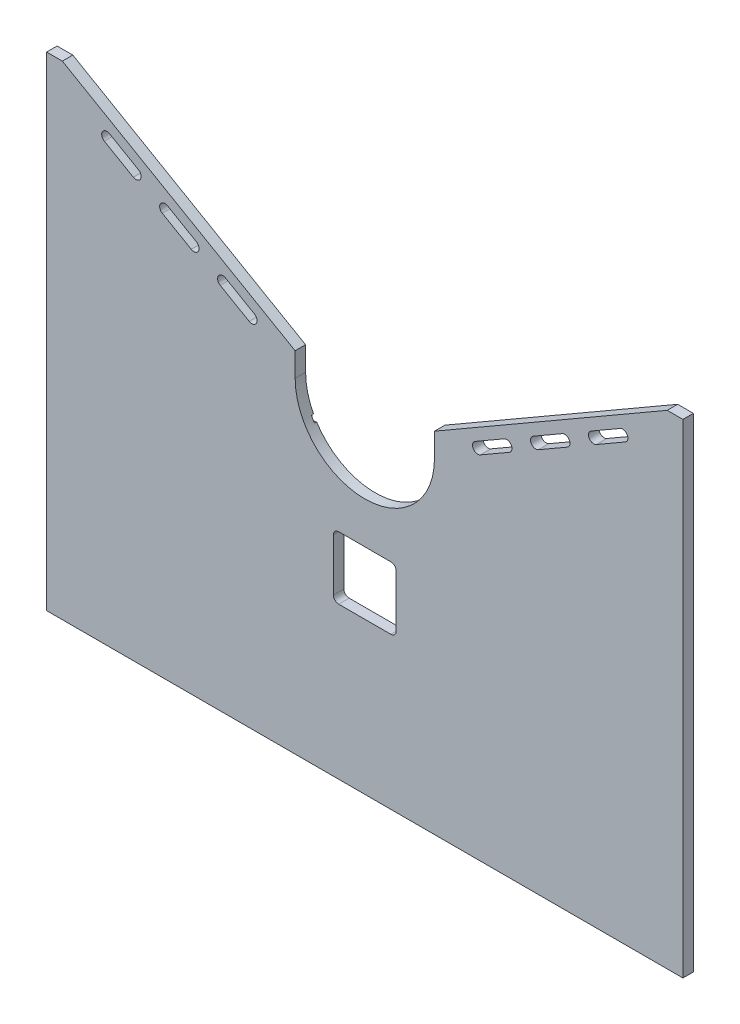
SolidWorks part; units mm, degrees
ref_plane "Front Plane" through (0, 0, 0) normal (0, 0, 1) x (1, 0, 0)
ref_plane "Top Plane" through (0, 0, 0) normal (0, 1, 0) x (1, 0, 0)
ref_plane "Right Plane" through (0, 0, 0) normal (1, 0, 0) x (0, 0, -1)
sketch "Sketch1" plane through (0, 0, 1081.9039) normal (0, 0, 1) x (1, 0, 0)
  line L1 (779.1923, 749.5089) -> (760.1423, 749.5089)
  line L2 (477.497, 557.3071) -> (477.497, 586.2509)
  line L6 (779.1923, 749.5089) -> (779.1923, 162.0069)
  line L7 (779.1923, 162.0069) -> (6.5497, 162.0069)
  line L10 (6.5497, 749.5089) -> (6.5497, 162.0069)
  line L11 (308.333, 557.3071) -> (308.289, 586.2255)
  line L13 (6.5497, 749.5089) -> (25.5997, 749.5089)
  line L14 (477.497, 586.2509) -> (760.1423, 749.5089)
  line L15 (308.289, 586.2255) -> (25.5997, 749.5089)
  circle A0 centre (392.915, 557.3071) radius 84.582 construction
  arc A1 (477.497, 557.3071) -> (308.333, 557.3071) centre (392.915, 557.3071) cw
  point P0 (0, 0)
  point P15 (392.871, 162.0069)
  dimension "D5" = 84.582
  dimension "D4" = 772.6426
  dimension "D3" = 395.3002
  dimension "D1" = 587.502
  dimension "D2" = 28.9438
  dimension "D6" = 19.05
  dimension "D7" = 19.05
  dimension "D9" = 30.011
  dimension "D10" = 30.011
extrude "Boss-Extrude1" add sketch "Sketch1" against normal blind 12.7
sketch "Sketch7" plane through (0, 0, 1069.2039) normal (0, 0, -1) x (-1, 0, 0)
  line L0 (-392.915, 557.3071) -> (-392.915, 347.8675) construction
  line L2 (-424.665, 346.1569) -> (-361.165, 346.1569)
  line L3 (-431.015, 352.5069) -> (-431.015, 416.0069)
  line L4 (-424.665, 422.3569) -> (-361.165, 422.3569)
  line L5 (-354.815, 352.5069) -> (-354.815, 416.0069)
  line L6 (-431.015, 346.1569) -> (-354.815, 422.3569) construction
  line L7 (-431.015, 422.3569) -> (-354.815, 346.1569) construction
  line L8 (-6.5497, 162.0069) -> (-779.1923, 162.0069) construction
  line L9 (-779.1923, 162.0069) -> (-779.1923, 749.5089) construction
  arc A0 (-424.665, 346.1569) -> (-431.015, 352.5069) centre (-424.665, 352.5069) cw
  arc A1 (-361.165, 346.1569) -> (-354.815, 352.5069) centre (-361.165, 352.5069) ccw
  arc A2 (-361.165, 422.3569) -> (-354.815, 416.0069) centre (-361.165, 416.0069) cw
  arc A3 (-431.015, 416.0069) -> (-424.665, 422.3569) centre (-424.665, 416.0069) cw
  point P3 (-392.915, 384.2569)
  dimension "D1" = 6.35
  dimension "D3" = 76.2
  dimension "D4" = 76.2
  dimension "D2" = 184.15
  dimension "D5" = 348.1773
extrude "Cut-Extrude5" cut sketch "Sketch7" against normal up to surface (12.7 mm away) up to face at (392.8842, 552.4558, 1081.9039)
sketch "Sketch9" plane through (0, 0, 1069.2039) normal (0, 0, -1) x (-1, 0, 0)
  line L0 (-392.915, 472.8521) -> (-392.915, 557.3071) construction
  line L1 (-392.915, 557.3071) -> (-466.1652, 515.0161) construction
  line L2 (-392.915, 557.3071) -> (-319.6648, 515.0161) construction
  arc A1 (-477.497, 557.3071) -> (-308.333, 557.3071) centre (-392.915, 557.3071) ccw construction
  circle A2 centre (-466.1652, 515.0161) radius 3.81
  circle A3 centre (-319.6648, 515.0161) radius 3.81
  dimension "D1" = 60
extrude "Cut-Extrude6" cut sketch "Sketch9" against normal blind 2.54
sketch "Sketch10" plane through (0, 0, 1069.2039) normal (0, 0, -1) x (-1, 0, 0)
  line L0 (-707.6027, 719.1758) -> (-717.1282, 702.677) construction
  line L1 (-760.1423, 749.5089) -> (-477.497, 586.2509) construction
  line L3 (-509.6574, 604.827) -> (-519.1548, 588.377) construction
  line L4 (-717.1282, 702.677) -> (-519.1548, 588.377) construction
  line L24 (-779.1923, 749.5089) -> (-760.1423, 749.5089) construction
  line L25 (-82.9192, 701.801) -> (-118.1145, 681.481)
  line L26 (-702.9108, 701.801) -> (-667.7155, 681.481)
  line L27 (-76.5692, 690.8024) -> (-111.7645, 670.4824)
  line L28 (-709.2608, 690.8024) -> (-674.0655, 670.4824)
  line L29 (-153.3098, 661.161) -> (-188.505, 640.841)
  line L30 (-638.8702, 650.1624) -> (-603.675, 629.8424)
  line L31 (-632.5202, 661.161) -> (-597.325, 640.841)
  line L32 (-568.4797, 609.5224) -> (-533.2844, 589.2024)
  line L33 (-562.1297, 620.521) -> (-526.9344, 600.201)
  line L34 (-146.9598, 650.1624) -> (-182.155, 629.8424)
  line L35 (-223.7003, 620.521) -> (-258.8956, 600.201)
  line L36 (-217.3503, 609.5224) -> (-252.5456, 589.2024)
  line L37 (-779.1923, 162.0069) -> (-779.1923, 749.5089) construction
  circle A0 centre (-706.0858, 696.3017) radius 6.35 construction
  circle A1 centre (-670.8905, 675.9817) radius 6.35 construction
  arc A19 (-82.9192, 701.801) -> (-76.5692, 690.8024) centre (-79.7442, 696.3017) cw
  circle A20 centre (-635.6952, 655.6617) radius 6.35 construction
  arc A21 (-118.1145, 681.481) -> (-111.7645, 670.4824) centre (-114.9395, 675.9817) ccw
  circle A22 centre (-600.5, 635.3417) radius 6.35 construction
  circle A23 centre (-565.3047, 615.0217) radius 6.35 construction
  circle A24 centre (-530.1094, 594.7017) radius 6.35 construction
  arc A25 (-702.9108, 701.801) -> (-709.2608, 690.8024) centre (-706.0858, 696.3017) ccw
  arc A26 (-667.7155, 681.481) -> (-674.0655, 670.4824) centre (-670.8905, 675.9817) cw
  arc A27 (-597.325, 640.841) -> (-603.675, 629.8424) centre (-600.5, 635.3417) cw
  arc A28 (-632.5202, 661.161) -> (-638.8702, 650.1624) centre (-635.6952, 655.6617) ccw
  arc A29 (-526.9344, 600.201) -> (-533.2844, 589.2024) centre (-530.1094, 594.7017) cw
  arc A30 (-562.1297, 620.521) -> (-568.4797, 609.5224) centre (-565.3047, 615.0217) ccw
  arc A31 (-153.3098, 661.161) -> (-146.9598, 650.1624) centre (-150.1348, 655.6617) cw
  arc A32 (-188.505, 640.841) -> (-182.155, 629.8424) centre (-185.33, 635.3417) ccw
  arc A33 (-223.7003, 620.521) -> (-217.3503, 609.5224) centre (-220.5253, 615.0217) cw
  arc A34 (-258.8956, 600.201) -> (-252.5456, 589.2024) centre (-255.7206, 594.7017) ccw
  dimension "D4" = 6.35
  dimension "D2" = 228.6
  dimension "D9" = 53.2072
  dimension "D1" = 73.1065
  dimension "D5" = 40.64
  dimension "D7" = 30
  dimension "D3" = 6
  dimension "D6" = 3
extrude "Cut-Extrude7" cut sketch "Sketch10" against normal up to surface (12.7 mm away) up to face at (392.915, 384.2569, 1081.9039)
equation "\"PETER_BALLEND_RADIUS\"= 0.25in"
equation "\"FACE_HEIGHT\" = 23.13"
equation "\"D1@Sketch1\"=\"FACE_HEIGHT\""
equation "\"FACE_BOTTOM\"=30.419"
equation "\"D4@Sketch1\"=\"FACE_BOTTOM\""
equation "\"FACE_TOP_HORIZONTAL_THRESHOLD\"=0.75"
equation "\"D6@Sketch1\"=\"FACE_TOP_HORIZONTAL_THRESHOLD\""
equation "\"D7@Sketch1\"=\"FACE_TOP_HORIZONTAL_THRESHOLD\""
equation "\"FIN_CAN_OUTER_RADIUS\"=3.33"
equation "\"D5@Sketch1\"=\"FIN_CAN_OUTER_RADIUS\""
equation "\"SEMICIRCLE_RADIAL_CENTER_FROM_BOTTOM\"= 12.713 + 2.85"
equation "\"D3@Sketch1\"=\"SEMICIRCLE_RADIAL_CENTER_FROM_BOTTOM\""
equation "\"CLAMP_SQUARE_HOLE_WIDTH\"=3"
equation "\"D4@Sketch7\"=\"CLAMP_SQUARE_HOLE_WIDTH\""
equation "\"D1@Sketch7\"=\"PETER_BALLEND_RADIUS\""
equation "\"CLAMP_SQUARE_BOTTOM_TO_BOTTOM_DISTANCE\" = 7.25"
equation "\"D2@Sketch7\"=\"CLAMP_SQUARE_BOTTOM_TO_BOTTOM_DISTANCE\""
equation "\"D3@Sketch7\"=\"CLAMP_SQUARE_HOLE_WIDTH\""
equation "\"WOOD_THICKNESS\"=0.5"
equation "\"D1@Boss-Extrude1\"=\"WOOD_THICKNESS\""
equation "\"TOP_SURFACE_TO_VERTICAL_CENTERLINE_ANGLE\"=60"
equation "\"D1@Sketch9\"=\"TOP_SURFACE_TO_VERTICAL_CENTERLINE_ANGLE\""
equation "\"LONG_INNER_FACE_DISTANCE\"=9"
equation "\"D2@Sketch10\"=\"LONG_INNER_FACE_DISTANCE\""
equation "\"GROOVE_HOLE_ONE_HORIZONTAL_PLACEMENT\"=2.87821"
equation "\"D1@Sketch10\"=\"GROOVE_HOLE_ONE_HORIZONTAL_PLACEMENT\""
equation "\"D4@Sketch10\"=\"PETER_BALLEND_RADIUS\""
equation "\"GROOVE_ARC_CENTER_TO_CENTER_DISTANCE\"=1.6"
equation "\"D5@Sketch10\"=\"GROOVE_ARC_CENTER_TO_CENTER_DISTANCE\""
equation "\"GROOVE_HOLE_ONE_VERTICAL_PLACEMENT\"=2.09477"
equation "\"D9@Sketch10\"=\"GROOVE_HOLE_ONE_VERTICAL_PLACEMENT\""
equation "\"SLANTED_EDGE_ANGLE\"=30"
equation "\"D7@Sketch10\"=\"SLANTED_EDGE_ANGLE\""
